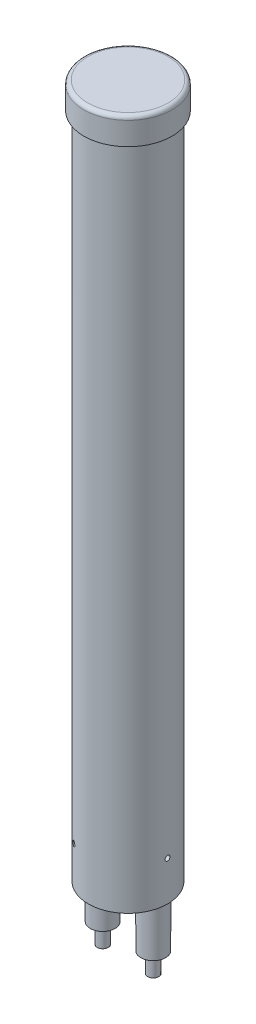
SolidWorks part; units mm, degrees
material "Custom Plastic"
ref_plane "Płaszczyzna przednia" through (0, 0, 0) normal (0, 0, 1) x (1, 0, 0)
ref_plane "Płaszczyzna górna" through (0, 0, 0) normal (0, 1, 0) x (1, 0, 0)
ref_plane "Płaszczyzna prawa" through (0, 0, 0) normal (1, 0, 0) x (0, 0, -1)
sketch "Sketch1" plane through (0, 0, 0) normal (0, 1, 0) x (1, 0, 0)
  circle A0 centre (0, 0) radius 20
  dimension "D1" = 40
extrude "Boss-Extrude1" add sketch "Sketch1" along normal blind 345
sketch "Sketch2" plane through (0, 345, 0) normal (0, 1, 0) x (1, 0, 0)
  circle A0 centre (0, 0) radius 22.25
  dimension "D1" = 44.5
extrude "Boss-Extrude2" add sketch "Sketch2" along normal blind 5 and the other way blind 8.5
fillet "Fillet1" radius 2 1 edges at (0, 350, 22.25)
ref_plane "Plane1" through (20, 0, 0) normal (1, 0, 0) x (0, 0, -1)
sketch "Sketch3" plane through (20, 0, 0) normal (1, 0, 0) x (0, 0, -1)
  line L0 (0, 0) -> (0, 20) construction
  circle A0 centre (0, 20) radius 1.25
  dimension "D2" = 2.5
  dimension "D1" = 20
extrude "Cut-Extrude1" cut sketch "Sketch3" against normal blind 5
pattern_circular "CirPattern1" count 3 every 120 about axis through (0, 0, 0) along (0, 1, 0) of "Cut-Extrude1"
sketch "Sketch4" plane through (0, 0, 0) normal (0, -1, 0) x (1, 0, 0)
  line L0 (12.75, 0) -> (0, 0) construction
  line L1 (0, 0) -> (-12.75, 0) construction
  circle A0 centre (-12.75, 0) radius 6.25
  circle A1 centre (12.75, 0) radius 6.25
  dimension "D1" = 25.5
  dimension "D2" = 12.5
extrude "Boss-Extrude3" add sketch "Sketch4" along normal blind 24
sketch "Sketch5" plane through (0, -24, 0) normal (0, -1, 0) x (1, 0, 0)
  circle A0 centre (-12.75, 0) radius 2.8
  circle A1 centre (12.75, 0) radius 2.8
  dimension "D1" = 5.6
extrude "Boss-Extrude4" add sketch "Sketch5" along normal blind 10
